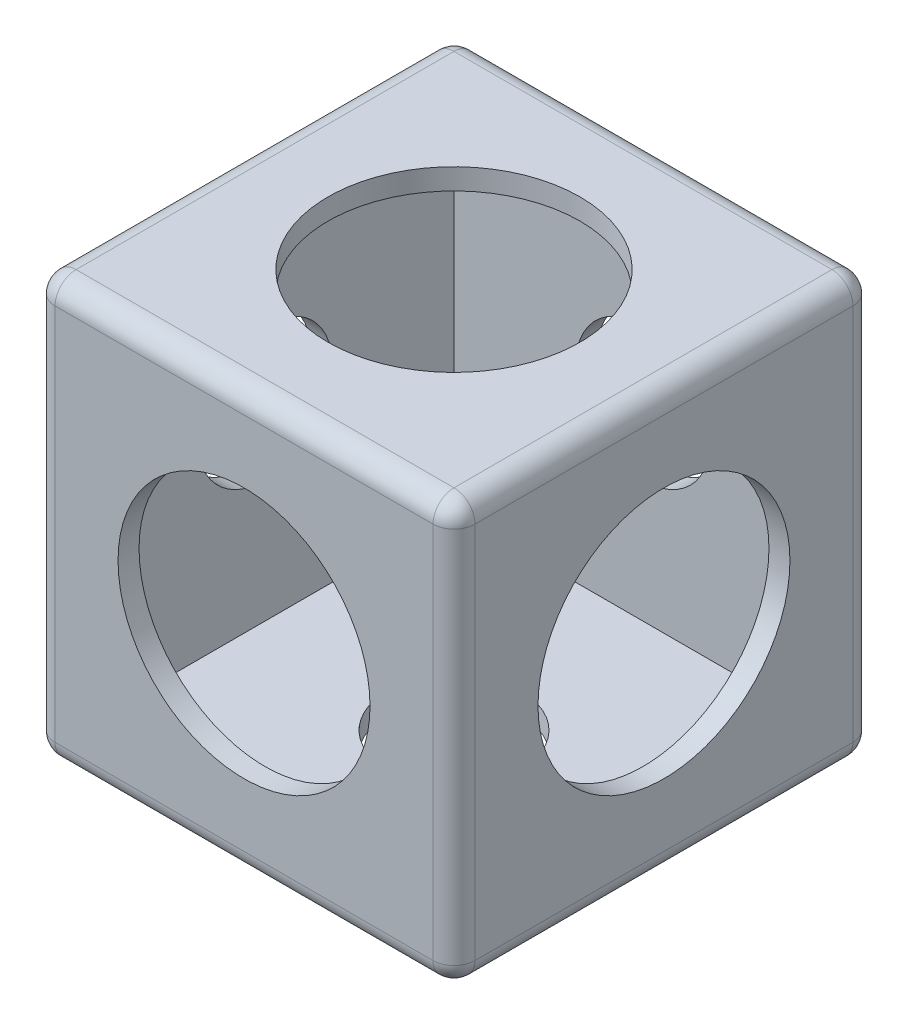
SolidWorks part; units mm, degrees
ref_plane "Front Plane" through (0, 0, 0) normal (0, 0, 1) x (1, 0, 0)
ref_plane "Top Plane" through (0, 0, 0) normal (0, 1, 0) x (1, 0, 0)
ref_plane "Right Plane" through (0, 0, 0) normal (1, 0, 0) x (0, 0, -1)
sketch "Sketch1" plane through (0, 0, 0) normal (0, 1, 0) x (1, 0, 0)
  line L1 (0, 0) -> (10, 0)
  line L2 (0, 0) -> (0, 10)
  line L3 (0, 10) -> (10, 10)
  line L4 (10, 0) -> (10, 10)
  circle A0 centre (5, 5) radius 1.6
extrude "Boss-Extrude1" add sketch "Sketch1" along normal blind 0.5
sketch "Sketch4" plane through (0, 0.5, 0) normal (0, 1, 0) x (1, 0, 0)
  line L0 (10, 10) -> (0, 10) construction
  line L1 (0.5, 0.5) -> (9.5, 0.5)
  line L2 (0.5, 0.5) -> (0.5, 9.5)
  line L3 (0.5, 9.5) -> (9.5, 9.5)
  line L4 (9.5, 0.5) -> (9.5, 9.5)
  line L5 (0, 0) -> (10, 0)
  line L6 (0, 0) -> (0, 10)
  line L7 (0, 10) -> (10, 10)
  line L8 (10, 0) -> (10, 10)
extrude "Boss-Extrude2" add sketch "Sketch4" along normal blind 9
sketch "Sketch5" plane through (0, 9.5, 0) normal (0, 1, 0) x (1, 0, 0)
  line L1 (0, 10) -> (10, 10)
  line L2 (0, 10) -> (0, 0)
  line L3 (0, 0) -> (10, 0)
  line L4 (10, 10) -> (10, 0)
  circle A0 centre (5, 5) radius 3
extrude "Boss-Extrude3" add sketch "Sketch5" along normal blind 0.5
sketch "Sketch6" plane through (10, 0, 0) normal (1, 0, 0) x (0, 0, -1)
  circle A0 centre (5, 5) radius 3
extrude "Cut-Extrude1" cut sketch "Sketch6" against normal blind 0.5
sketch "Sketch7" plane through (0, 0, 0) normal (0, 0, 1) x (1, 0, 0)
  circle A0 centre (5, 5) radius 3
extrude "Cut-Extrude2" cut sketch "Sketch7" against normal blind 0.5
sketch "Sketch8" plane through (0, 0, 0) normal (-1, 0, 0) x (0, 0, 1)
  circle A0 centre (-5, 5) radius 1.6
extrude "Cut-Extrude3" cut sketch "Sketch8" against normal blind 0.5
sketch "Sketch9" plane through (0, 0, -10) normal (0, 0, -1) x (-1, 0, 0)
  circle A0 centre (-5, 5) radius 1.6
extrude "Cut-Extrude4" cut sketch "Sketch9" against normal blind 0.5
fillet "Fillet5" radius 0.5 12 edges at (0, 0, -5) (0, 5, -10) (0, 5, 0) (0, 10, -5) (5, 10, 0) (10, 5, 0) (5, 0, 0) (10, 0, -5) (5, 0, -10) (10, 10, -5) (5, 10, -10) (10, 5, -10)
